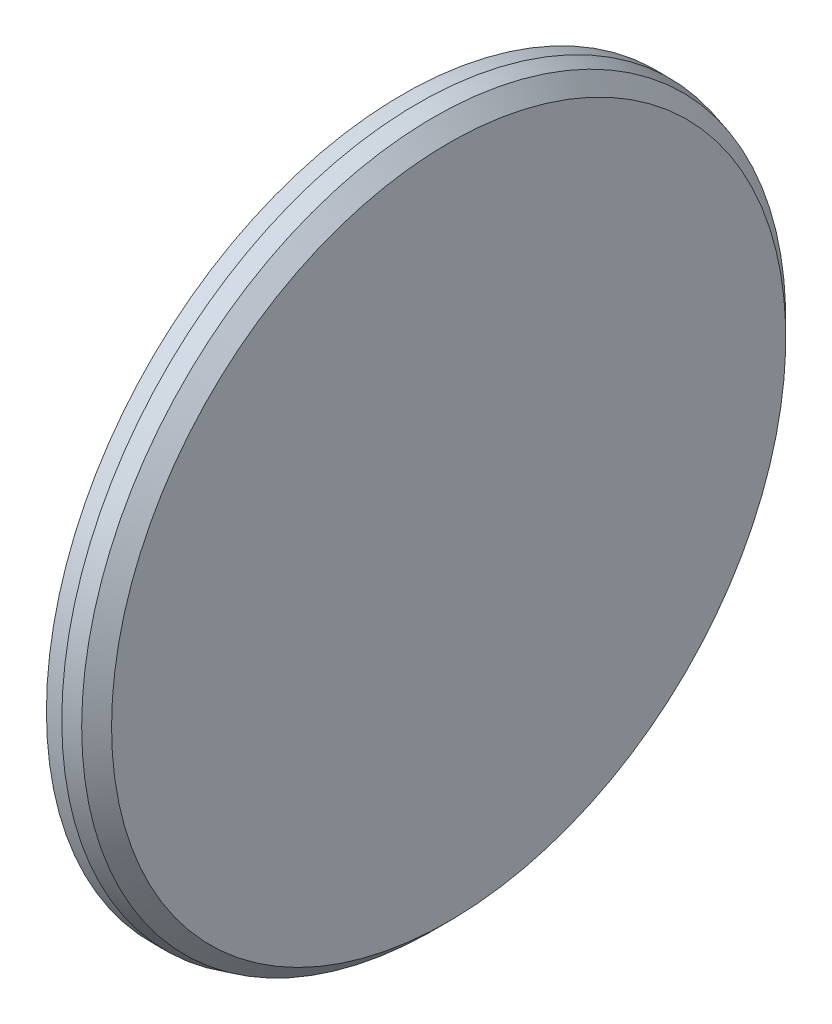
SolidWorks part; units mm, degrees
material "Alliage 1060"
ref_plane "Plan de face" through (0, 0, 0) normal (0, 0, 1) x (1, 0, 0)
ref_plane "Plan de dessus" through (0, 0, 0) normal (0, 1, 0) x (1, 0, 0)
ref_plane "Plan de droite" through (0, 0, 0) normal (1, 0, 0) x (0, 0, -1)
sketch "Esquisse2" plane through (0, 0, 0) normal (0, 0, 1) x (1, 0, 0)
  line L0 (19.3839, 93.6847) -> (19.3839, 48.6847)
  line L1 (19.3839, 48.6847) -> (49.3839, 48.6847)
  line L2 (49.3839, 48.6847) -> (49.3839, -271.3153)
  line L3 (49.3839, -271.3153) -> (-0.6161, -271.3153)
  line L4 (-0.6161, -271.3153) -> (-0.6161, -371.3153)
  line L6 (79.3839, -371.3153) -> (79.3839, 68.6847)
  line L8 (79.3839, 68.6847) -> (59.8743, 88.1943)
  line L9 (59.8743, 88.1943) -> (39.3839, 93.6847)
  line L10 (39.3839, 93.6847) -> (19.3839, 93.6847)
  line L18 (-0.6161, -371.3153) -> (79.3839, -371.3153)
  dimension "D2" = 30
  dimension "D4" = 135
  dimension "D5" = 165
  dimension "D6" = 45
  dimension "D7" = 20
  dimension "D8" = 60
  dimension "D3" = 80
  dimension "D1" = 100
  dimension "D9" = 465
  dimension "D10" = 440
revolve "Révolution1" add sketch "Esquisse2" angle 360 about L18
sketch "Esquisse3" plane through (49.3839, 0, 0) normal (-1, 0, 0) x (0, 0, 1)
  line L0 (0, -271.3153) -> (0, -460.2772) construction
  line L1 (100, -371.3153) -> (-100, -371.3153) construction
  line L2 (0, -271.3153) -> (-20, -271.3153) construction
  line L3 (-20, -265.4853) -> (-20, -20.3168)
  line L4 (20, 37.5856) -> (20, -176.9047)
  line L5 (24, -274.2381) -> (24, -274.8915)
  line L6 (20, -176.9047) -> (20, -265.4853)
  circle A0 centre (0, -371.3153) radius 100 construction
  circle A1 centre (0, -371.3153) radius 100 construction
  circle A2 centre (0, -371.3153) radius 420 construction
  circle A3 centre (0, -371.3153) radius 100
  arc A4 (27.2727, -275.1062) -> (20, -265.4853) centre (30, -265.4853) cw
  arc A5 (-20, -265.4853) -> (-27.2727, -275.1062) centre (-30, -265.4853) cw
  circle A6 centre (0, -371.3153) radius 420
  arc A7 (30.7317, 47.5588) -> (20, 37.5856) centre (30, 37.5856) ccw
  arc A8 (-93.3333, 38.183) -> (-20, -20.3168) centre (-80, -20.3168) cw
  circle M4 centre (0, -371.3153) radius 100
  circle M5 centre (0, -371.3153) radius 420
  dimension "D2" = 10
  dimension "D3" = 10
  dimension "D4" = 10
  dimension "D5" = 60
  dimension "D1" = 40
extrude "Boss.-Extru.1" add sketch "Esquisse3" along normal blind 20 contours A8 L3 A5 A4 L6 L4 A7 M5 M4
pattern_circular "Répétition circulaire1" count 9 over 360 about axis through (0, -371.3153, 0) along (1, 0, 0) of "Boss.-Extru.1"
equation "\"A\"= 60"
equation "\"B\"= 930"
equation "\"D8@Esquisse2\"=\"A\""
equation "\"D3@Esquisse2\"=\"A\"+20"
equation "\"D9@Esquisse2\"=(\"B\")/2"
equation "\"D10@Esquisse2\"=(\"B\"-50)/2"
